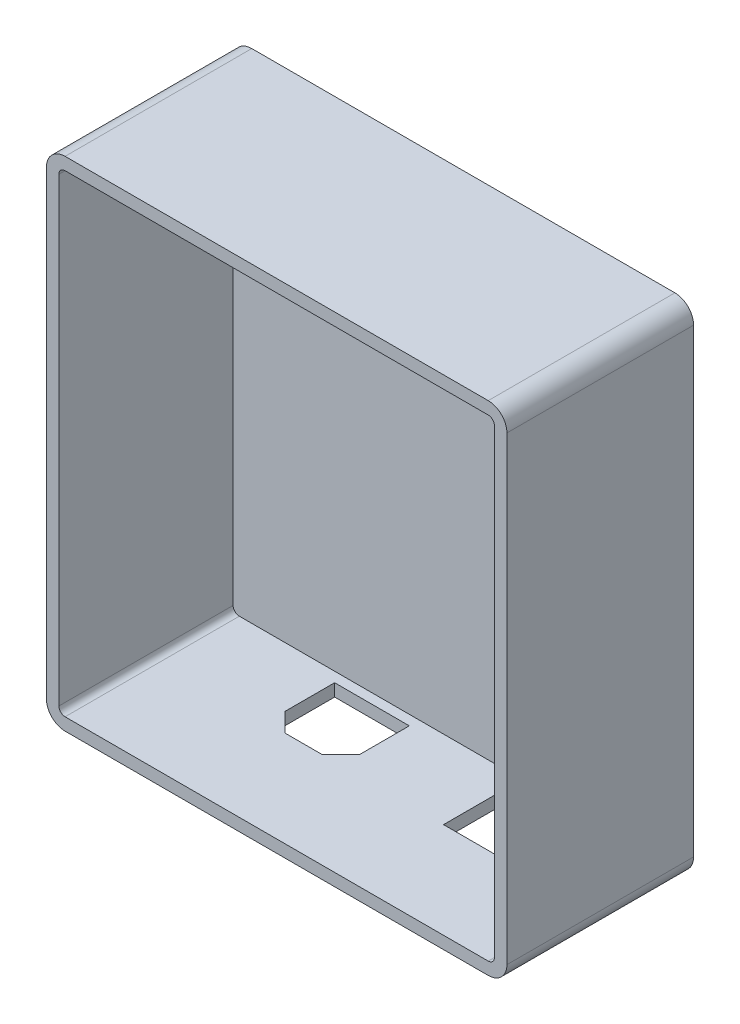
SolidWorks part; units mm, degrees
ref_plane "Front Plane" through (0, 0, 0) normal (0, 0, 1) x (1, 0, 0)
ref_plane "Top Plane" through (0, 0, 0) normal (0, 1, 0) x (1, 0, 0)
ref_plane "Right Plane" through (0, 0, 0) normal (1, 0, 0) x (0, 0, -1)
sketch "Sketch2" plane through (0, 0, 0) normal (0, 0, 1) x (1, 0, 0)
  line L1 (-28.9172, 20.795) -> (39.0828, 20.795)
  line L2 (-31.9172, 17.795) -> (-31.9172, -56.205)
  line L3 (-28.9172, -59.205) -> (39.0828, -59.205)
  line L4 (42.0828, 17.795) -> (42.0828, -56.205)
  arc A0 (-31.9172, -56.205) -> (-28.9172, -59.205) centre (-28.9172, -56.205) ccw
  arc A1 (39.0828, -59.205) -> (42.0828, -56.205) centre (39.0828, -56.205) ccw
  arc A2 (39.0828, 20.795) -> (42.0828, 17.795) centre (39.0828, 17.795) cw
  arc A3 (-28.9172, 20.795) -> (-31.9172, 17.795) centre (-28.9172, 17.795) ccw
  point P8 (42.0828, -59.205)
  point P11 (42.0828, 20.795)
  point P14 (-31.9172, 20.795)
  dimension "D3" = 3
  dimension "D1" = 74
  dimension "D2" = 80
extrude "Boss-Extrude2" add sketch "Sketch2" along normal blind 30
sketch "Sketch7" plane through (0, 0, 30) normal (0, 0, 1) x (1, 0, 0)
  line L8 (-28.9172, -57.205) -> (39.0828, -57.205)
  line L9 (40.0828, -56.205) -> (40.0828, 17.795)
  line L10 (39.0828, 18.795) -> (-28.9172, 18.795)
  line L11 (-29.9172, 17.795) -> (-29.9172, -56.205)
  line L12 (-28.9172, -57.205) -> (39.0828, -57.205)
  line L13 (40.0828, -56.205) -> (40.0828, 17.795)
  line L14 (39.0828, 18.795) -> (-28.9172, 18.795)
  line L15 (-29.9172, 17.795) -> (-29.9172, -56.205)
  arc A8 (-29.9172, -56.205) -> (-28.9172, -57.205) centre (-28.9172, -56.205) ccw
  arc A9 (39.0828, -57.205) -> (40.0828, -56.205) centre (39.0828, -56.205) ccw
  arc A10 (40.0828, 17.795) -> (39.0828, 18.795) centre (39.0828, 17.795) ccw
  arc A11 (-28.9172, 18.795) -> (-29.9172, 17.795) centre (-28.9172, 17.795) ccw
  arc A12 (-29.9172, -56.205) -> (-28.9172, -57.205) centre (-28.9172, -56.205) ccw
  arc A13 (39.0828, -57.205) -> (40.0828, -56.205) centre (39.0828, -56.205) ccw
  arc A14 (40.0828, 17.795) -> (39.0828, 18.795) centre (39.0828, 17.795) ccw
  arc A15 (-28.9172, 18.795) -> (-29.9172, 17.795) centre (-28.9172, 17.795) ccw
  dimension "D1" = 2
extrude "Cut-Extrude3" cut sketch "Sketch7" against normal blind 28
sketch "Sketch10" plane through (0, -59.205, 0) normal (0, -1, 0) x (1, 0, 0)
  line L0 (-12, 11.6) -> (-9.0019, 14.5981)
  line L1 (-9.0019, 14.5981) -> (-3.0019, 14.5981)
  line L2 (-3.0019, 14.5981) -> (0, 11.6037)
  line L3 (0, 11.6037) -> (0, 3.6)
  line L4 (0, 3.6) -> (-12, 3.6)
  line L5 (-12, 3.6) -> (-12, 11.6)
  line L6 (-28.9172, 0) -> (39.0828, 0) construction
  line L7 (16.5, 14.6) -> (25.5, 14.6)
  line L8 (16.5, 14.6) -> (16.5, 3.6)
  line L9 (16.5, 3.6) -> (25.5, 3.6)
  line L10 (25.5, 14.6) -> (25.5, 3.6)
  dimension "D1" = 4.24
  dimension "D2" = 4.24
  dimension "D3" = 16.5
  dimension "D4" = 9
  dimension "D5" = 11
  dimension "D6" = 6
  dimension "D7" = 8
  dimension "D8" = 12
  dimension "D9" = 3.6
  dimension "D10" = 3.6
extrude "Cut-Extrude4" cut sketch "Sketch10" against normal blind 3
sketch "Sketch11" plane through (0, -59.205, 0) normal (0, -1, 0) x (1, 0, 0)
  line L1 (-12, 11.6) -> (-12, 3.6)
  line L2 (-12, 3.6) -> (0, 3.6)
  line L3 (0, 3.6) -> (0, 11.6037)
  line L4 (0, 11.6037) -> (-3.0019, 14.5981)
  line L5 (-3.0019, 14.5981) -> (-9.0019, 14.5981)
  line L6 (-9.0019, 14.5981) -> (-12, 11.6)
  line L7 (16.5, 14.6) -> (16.5, 3.6)
  line L8 (16.5, 3.6) -> (25.5, 3.6)
  line L9 (25.5, 3.6) -> (25.5, 14.6)
  line L10 (25.5, 14.6) -> (16.5, 14.6)
  line L11 (-31.9172, 30) -> (-31.9172, 0)
  line L12 (-31.9172, 0) -> (42.0828, 0)
  line L13 (42.0828, 0) -> (42.0828, 30)
  line L14 (42.0828, 30) -> (-31.9172, 30)
  dimension "D1" = 8
  dimension "D2" = 6
  dimension "D3" = 2.9981
  dimension "D4" = 12
  dimension "D5" = 11
  dimension "D6" = 9
  dimension "D7" = 19.9172
  dimension "D8" = 3.6
  dimension "D9" = 15.4019
  dimension "D10" = 3.6
  dimension "D11" = 16.5828
